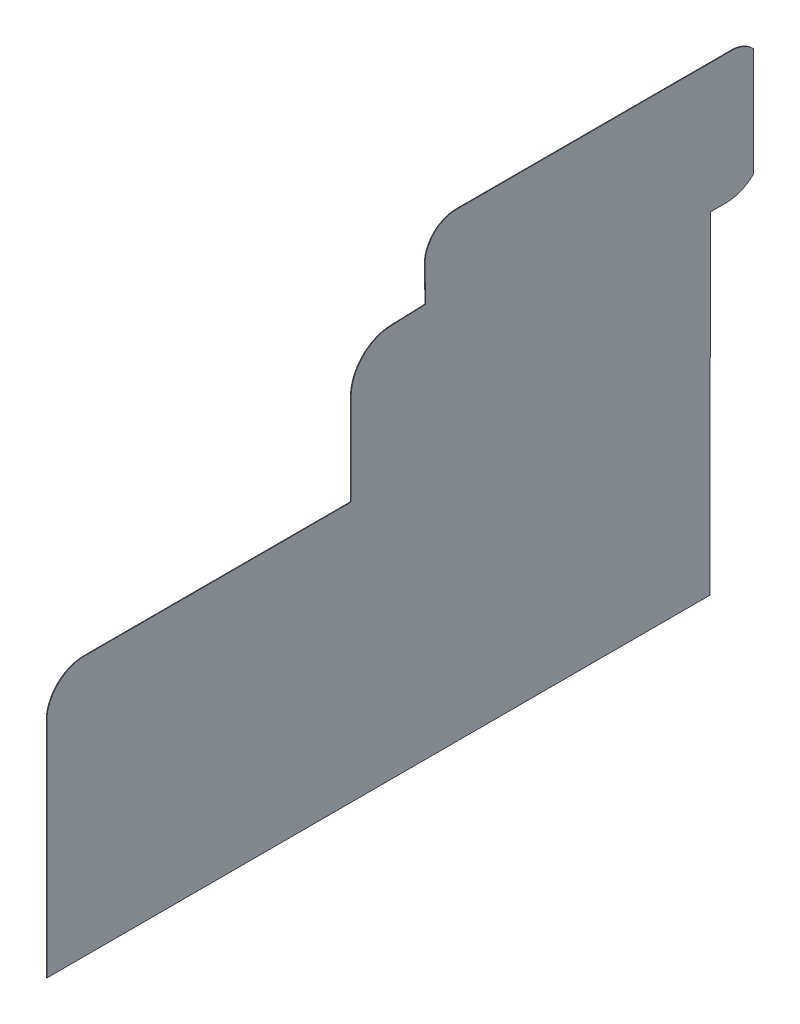
SolidWorks part; units mm, degrees
ref_plane "Piano frontale" through (0, 0, 0) normal (0, 0, 1) x (1, 0, 0)
ref_plane "Piano superiore" through (0, 0, 0) normal (0, 1, 0) x (1, 0, 0)
ref_plane "Piano destro" through (0, 0, 0) normal (1, 0, 0) x (0, 0, -1)
other "Grafica1"
other "Grafica (Chiusa) -1"
other "Grafica (Chiusa) -2"
other "Grafica (Chiusa) -3"
other "Grafica (Chiusa) -4"
other "Grafica (Chiusa) -5"
other "Grafica (Chiusa) -6"
sketch "Schizzo1" plane through (0, 0, 0) normal (1, 0, 0) x (0, 0, -1)
  line L0 (-1.1649, 0) -> (-0.072, 0)
  line L1 (-0.072, 0) -> (-0.0715, 0.5466)
  line L2 (-0.0715, 0.5466) -> (-0.0461, 0.5466)
  line L3 (-1.1649, 0) -> (-1.1649, 0.3725)
  line L4 (-1.1031, 0.4287) -> (-0.6636, 0.4287)
  line L5 (-0.6636, 0.4287) -> (-0.6636, 0.5791)
  line L6 (-0.5975, 0.6475) -> (-0.5472, 0.6492)
  line L7 (-0.5417, 0.7018) -> (-0.5409, 0.6497)
  line L8 (-0.5472, 0.6492) -> (-0.5409, 0.6497)
  line L9 (-0.4895, 0.7596) -> (-0.0362, 0.7596)
  line L10 (-0.0001, 0.7436) -> (-0.0001, 0.5654)
  line L11 (-0.5472, 0.6492) -> (-0.5409, 0.6497)
  arc A0 (-1.1031, 0.4287) -> (-1.1649, 0.3725) centre (-1.1031, 0.3665) ccw
  arc A1 (-1.1031, 0.4287) -> (-1.1649, 0.3725) centre (-1.1031, 0.3665) ccw
  arc A2 (-0.5975, 0.6475) -> (-0.6636, 0.5791) centre (-0.5952, 0.5791) ccw
  arc A3 (-0.4895, 0.7596) -> (-0.5417, 0.7018) centre (-0.4895, 0.7072) ccw
  arc A4 (-0.0362, 0.7596) -> (-0.0001, 0.7436) centre (-0.0362, 0.7109) cw
  arc A5 (-0.0461, 0.5466) -> (-0.0001, 0.5654) centre (-0.046, 0.6122) ccw
  point P0 (-1.1649, 0.3725)
  point P1 (-1.1031, 0.4287)
  point P3 (-0.6636, 0.4287)
  point P4 (-0.6636, 0.5791)
  point P5 (-0.5975, 0.6475)
  point P6 (-0.5472, 0.6492)
  point P8 (-0.5417, 0.7018)
  point P9 (-0.5421, 0.6497)
  point P10 (-0.4895, 0.7596)
  point P11 (-0.0362, 0.7596)
  point P13 (-0.0001, 0.7436)
  point P15 (-0.0001, 0.5654)
  point P16 (-0.0461, 0.5466)
  point P17 (-0.0715, 0.5466)
  point P19 (-0.072, 0)
  point P20 (-1.1649, 0)
  point P37 (-1.1649, 0)
  point P46 (-1.1649, 0)
  dimension "D1" = 0.4395
  dimension "D2" = 0.0621
  dimension "D3" = 0.0684
  dimension "D9" = 0.0656
  dimension "D4" = 0.0503
  dimension "D5" = 0.0521
  dimension "D6" = 0.4286
  dimension "D7" = 0.5466
  dimension "D8" = 0.1782
  dimension "D10" = 0.0487
  dimension "D11" = 0.0719
  dimension "D12" = 0.0063
extrude "Estrusione-Estrusione1" add sketch "Schizzo1" along normal blind 0.001 contours L2 A5 L10 A4 L9 A3 L7 L8 L6 A2 L5 L4 A0 L3 L0 L1
